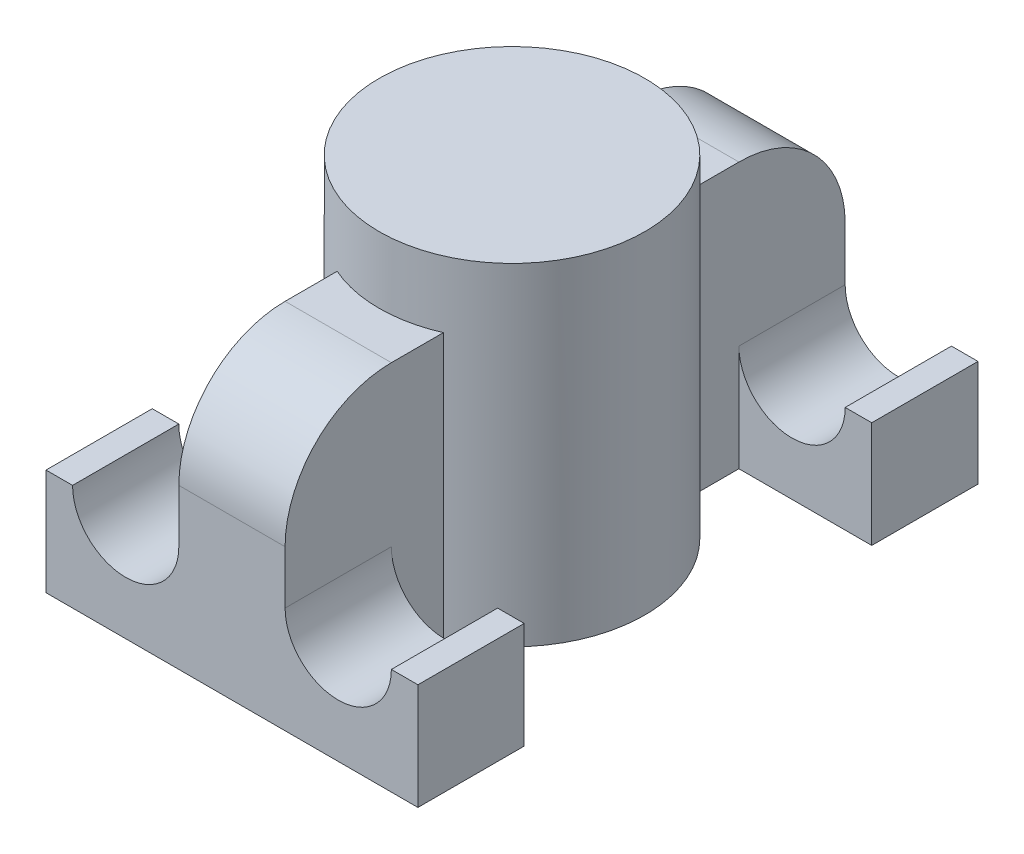
SolidWorks part; units mm, degrees
ref_plane "Front Plane" through (0, 0, 0) normal (0, 0, 1) x (1, 0, 0)
ref_plane "Top Plane" through (0, 0, 0) normal (0, 1, 0) x (1, 0, 0)
ref_plane "Right Plane" through (0, 0, 0) normal (1, 0, 0) x (0, 0, -1)
sketch "Sketch2" plane through (0, 0, 0) normal (0, 1, 0) x (1, 0, 0)
  line L1 (-4, 21.0826) -> (4, 21.0826)
  line L2 (-4, 21.0826) -> (-4, -21.0826)
  line L3 (-4, -21.0826) -> (4, -21.0826)
  line L4 (4, 21.0826) -> (4, -21.0826)
  point P4 (0, 21.0826)
  point P6 (-4, 0)
  dimension "D1" = 8
extrude "Boss-Extrude3" add sketch "Sketch2" along normal blind 20
sketch "Sketch4" plane through (0, 20, 0) normal (0, 1, 0) x (-1, 0, 0)
  circle A0 centre (0, 0) radius 10
  dimension "D1" = 20
extrude "Boss-Extrude4" add sketch "Sketch4" along normal blind 5 and the other way blind 20
hole_wizard "Hole1" positions "Sketch8" profile "Sketch9" legacy
sketch "Sketch8" plane through (0, 0, 0) normal (0, -1, 0) x (1, 0, 0)
  point P1 (0, 0)
sketch "Sketch9" plane through (0, 0, 0) normal (1, 0, 0) x (0, 0, -1)
  line L0 (0, 0) -> (0, 20)
  line L1 (0, 20) -> (5, 15)
  line L2 (5, 15) -> (5, 0)
  line L4 (5, 0) -> (0, 0)
  line L6 (0, 20) -> (-5, 15) construction
  line L7 (0, -4.2442) -> (0, 117.3081) construction
  dimension "Diameter" = 10
  dimension "Depth" = 15
  dimension "Drill Angle" = 90
sketch "Sketch10" plane through (0, 0, 21.0826) normal (0, 0, 1) x (1, 0, 0)
  line L0 (-4, 0) -> (-14, 0)
  line L1 (-14, 0) -> (-14, 8)
  line L2 (-14, 8) -> (-12, 8)
  line L3 (-4, 20) -> (-4, 0) construction
  line L5 (-4, 8) -> (-4, 0)
  arc A0 (-12, 8) -> (-4, 8) centre (-8, 8) ccw
  dimension "D2" = 4
  dimension "D1" = 10
  dimension "D3" = 8
extrude "Boss-Extrude5" add sketch "Sketch10" against normal blind 8
mirror "Mirror2" about plane through (0, 0, 0) normal (1, 0, 0) of "Boss-Extrude5"
mirror "Mirror3" about plane through (0, 0, 0) normal (0, 0, 1) of "Mirror2", "Boss-Extrude5"
fillet "Fillet1" radius 8 2 edges at (0, 20, -21.0826) (0, 20, 21.0826)
